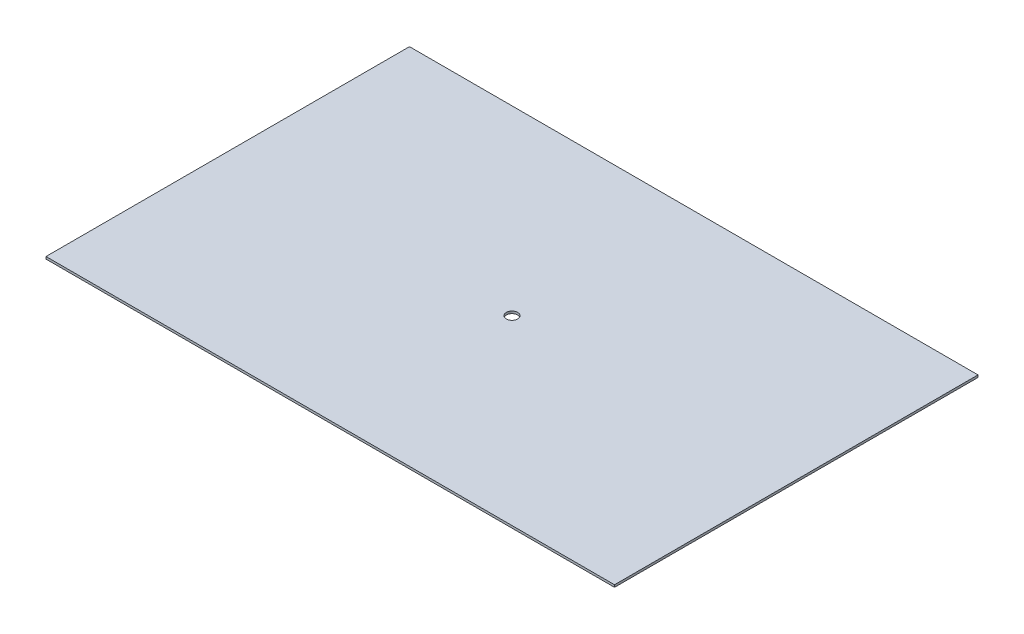
SolidWorks part; units mm, degrees
ref_plane "Front Plane" through (0, 0, 0) normal (0, 0, 1) x (1, 0, 0)
ref_plane "Top Plane" through (0, 0, 0) normal (0, 1, 0) x (1, 0, 0)
ref_plane "Right Plane" through (0, 0, 0) normal (1, 0, 0) x (0, 0, -1)
sketch "Sketch1" plane through (0, 0, 0) normal (1, 0, 0) x (0, 0, -1)
  line L1 (-124.7625, -44.7625) -> (124.7625, -44.7625)
  line L2 (-124.7625, -44.7625) -> (-124.7625, 44.7625)
  line L3 (-124.7625, 44.7625) -> (124.7625, 44.7625)
  line L4 (124.7625, -44.7625) -> (124.7625, 44.7625)
  line L5 (-124.7625, -44.7625) -> (124.7625, 44.7625) construction
  line L6 (-124.7625, 44.7625) -> (124.7625, -44.7625) construction
  circle A0 centre (0, 0) radius 2.5
  point P0 (0, 0)
  dimension "D3" = 5
  dimension "D1" = 249.525
  dimension "D2" = 89.525
extrude "Boss-Extrude1" [suppressed] add sketch "Sketch1" along normal blind 1
sketch "Sketch2" plane through (0, 0, 0) normal (0, 1, 0) x (1, 0, 0)
  line L1 (-124.7625, -79.7625) -> (124.7625, -79.7625)
  line L2 (-124.7625, -79.7625) -> (-124.7625, 79.7625)
  line L3 (-124.7625, 79.7625) -> (124.7625, 79.7625)
  line L4 (124.7625, -79.7625) -> (124.7625, 79.7625)
  line L5 (-124.7625, -79.7625) -> (124.7625, 79.7625) construction
  line L6 (-124.7625, 79.7625) -> (124.7625, -79.7625) construction
  circle A0 centre (0, 0) radius 2.5
  point P0 (0, 0)
  dimension "D3" = 5
  dimension "D1" = 249.525
  dimension "D2" = 159.525
extrude "Boss-Extrude2" add sketch "Sketch2" along normal blind 1
